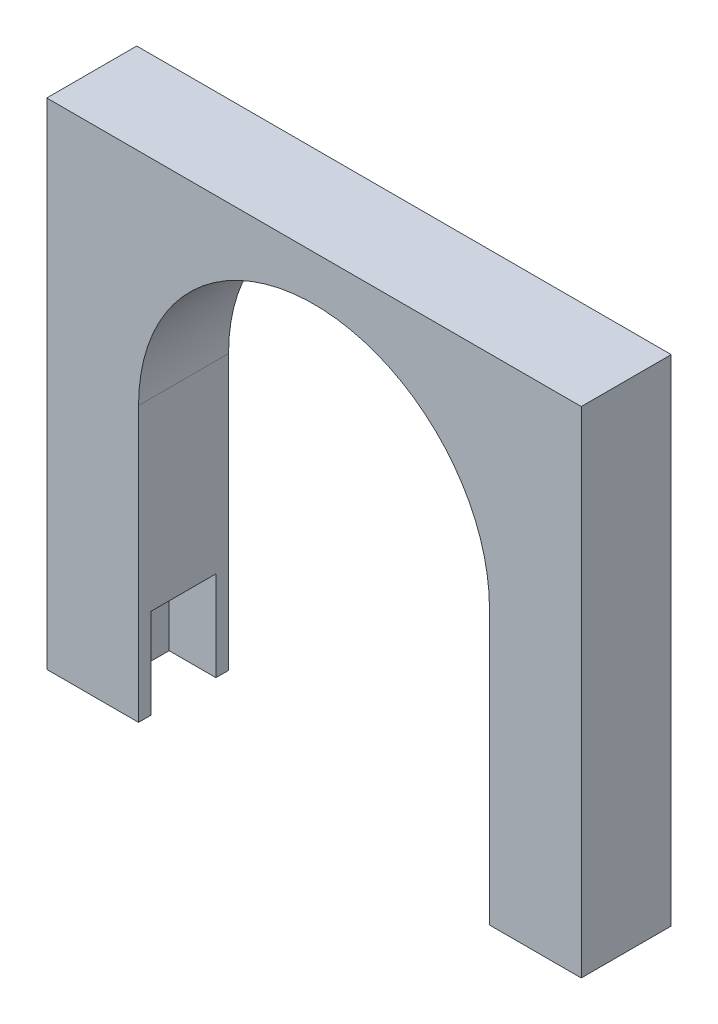
SolidWorks part; units mm, degrees
ref_plane "Alzado" through (0, 0, 0) normal (0, 0, 1) x (1, 0, 0)
ref_plane "Planta" through (0, 0, 0) normal (0, 1, 0) x (1, 0, 0)
ref_plane "Vista lateral" through (0, 0, 0) normal (1, 0, 0) x (0, 0, -1)
sketch "Croquis2" plane through (0, 0, 0) normal (0, 0, 1) x (1, 0, 0)
  line L0 (-19.5, 0) -> (-29.7, 0)
  line L1 (-29.7, 0) -> (-29.7, 55)
  line L2 (-29.7, 55) -> (29.7, 55)
  line L3 (29.7, 55) -> (29.7, 0)
  line L4 (29.7, 0) -> (19.5, 0)
  line L5 (0, 30.5) -> (0, 0) construction
  line L6 (-19.5, 0) -> (-19.5, 30.5)
  line L7 (19.5, 0) -> (19.5, 30.5)
  arc A0 (19.5, 0) -> (-19.5, 0) centre (0, 0) ccw construction
  arc A2 (19.5, 30.5) -> (-19.5, 30.5) centre (0, 30.5) ccw
  dimension "D1" = 39
  dimension "D4" = 30.5
  dimension "D2" = 10.2
  dimension "D3" = 55
  dimension "D5" = 30.5
  dimension "D7" = 39
extrude "Saliente-Extruir1" add sketch "Croquis2" along normal blind 10
sketch "Croquis3" plane through (0, 0, 0) normal (0, -1, 0) x (1, 0, 0)
  line L3 (19.5, 5) -> (19.5, 8.6)
  line L9 (19.5, 10) -> (19.5, 0) construction
  line L10 (19.5, 8.6) -> (24.7, 8.6)
  line L11 (24.7, 8.6) -> (24.7, 1.4)
  line L12 (24.7, 1.4) -> (19.5, 1.4)
  line L13 (19.5, 10) -> (19.5, 0) construction
  line L14 (19.5, 1.4) -> (19.5, 5)
  line L15 (0, -55) -> (0, 55) construction
  line L16 (-24.7, 1.4) -> (-19.5, 1.4)
  line L17 (-24.7, 8.6) -> (-24.7, 1.4)
  line L18 (-19.5, 8.6) -> (-24.7, 8.6)
  line L19 (-19.5, 5) -> (-19.5, 8.6)
  line L20 (-19.5, 1.4) -> (-19.5, 5)
  dimension "D1" = 5.2
  dimension "D2" = 7.2
  dimension "D3" = 3.6
extrude "Cortar-Extruir1" cut sketch "Croquis3" against normal blind 10
sketch "Croquis4" plane through (0, 0, 10) normal (0, 0, 1) x (1, 0, 0)
  line L0 (-29.7, 0) -> (-19.5, 0) construction
  line L1 (-29.7, 0) -> (-19.5, 0)
